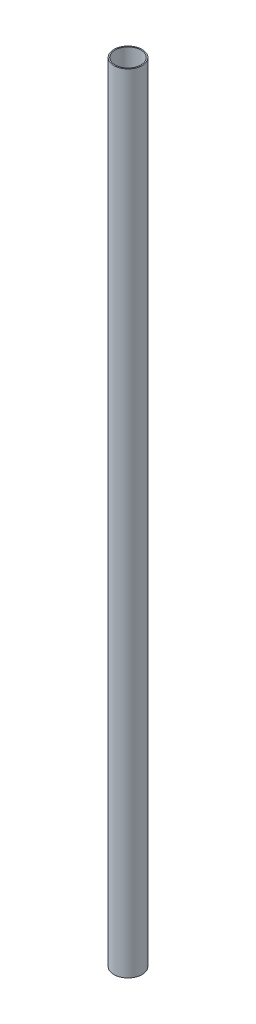
SolidWorks part; units mm, degrees
ref_plane "Front Plane" through (0, 0, 0) normal (0, 0, 1) x (1, 0, 0)
ref_plane "Top Plane" through (0, 0, 0) normal (0, 1, 0) x (1, 0, 0)
ref_plane "Right Plane" through (0, 0, 0) normal (1, 0, 0) x (0, 0, -1)
sketch "Sketch1" plane through (0, 0, 0) normal (0, 1, 0) x (1, 0, 0)
  circle A0 centre (0, 0) radius 12.5
  dimension "D1" = 25
extrude "Boss-Extrude1" add sketch "Sketch1" along normal blind 700
shell "Shell1" thickness 1
